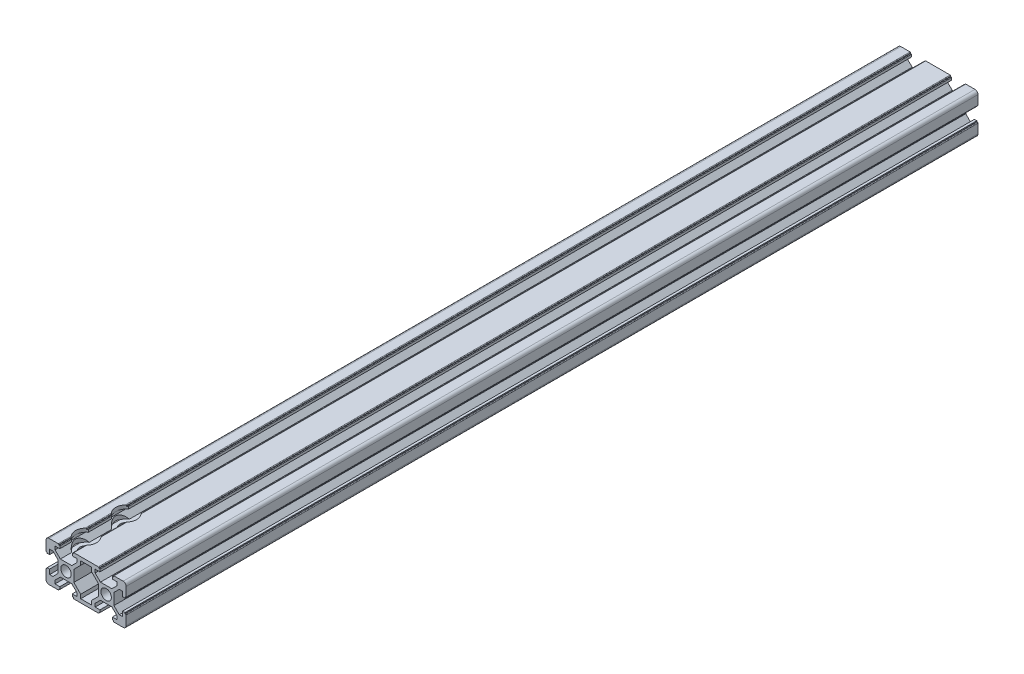
SolidWorks part; units mm, degrees
ref_plane "前视基准面" through (0, 0, 0) normal (0, 0, 1) x (1, 0, 0)
ref_plane "上视基准面" through (0, 0, 0) normal (0, 1, 0) x (1, 0, 0)
ref_plane "右视基准面" through (0, 0, 0) normal (1, 0, 0) x (0, 0, -1)
sketch "草图1" plane through (0, 0, 0) normal (0, 0, 1) x (1, 0, 0)
  line L0 (0, 0) -> (0, -41497.3383) construction
  line L1 (0, 0) -> (41497.3383, 0) construction
  line L2 (-13.9, 0) -> (-13.9, 2.8393)
  line L3 (-13.9, 2.8393) -> (-16.5607, 5.5)
  line L4 (-16.5607, 5.5) -> (-18.2, 5.5)
  line L5 (-18.2, 5.5) -> (-18.2, 3.1)
  line L6 (-18.2, 3.1) -> (-19.4, 3.1)
  line L7 (-19.4, 3.1) -> (-19.4, 3.6)
  line L8 (-19.4, 3.6) -> (-20, 3.6)
  line L9 (-20, 3.6) -> (-20, 10)
  line L10 (-20, 10) -> (-13.6, 10)
  line L11 (-13.6, 10) -> (-13.6, 9.4)
  line L12 (-13.6, 9.4) -> (-13.1, 9.4)
  line L13 (-13.1, 9.4) -> (-13.1, 8.2)
  line L14 (-13.1, 8.2) -> (-15.5, 8.2)
  line L15 (-15.5, 6.5607) -> (-12.8393, 3.9)
  line L16 (-12.8393, 3.9) -> (-7.1607, 3.9)
  line L17 (-4.5, 6.5607) -> (-7.1607, 3.9)
  line L18 (-4.5, 6.5607) -> (-4.5, 8.2)
  line L19 (-4.5, 8.2) -> (-6.9, 8.2)
  line L20 (-6.9, 8.2) -> (-6.9, 9.4)
  line L21 (-6.9, 9.4) -> (-6.4, 9.4)
  line L22 (-6.4, 9.4) -> (-6.4, 10)
  line L23 (-6.4, 10) -> (6.4, 10)
  line L24 (-15.5, 8.2) -> (-15.5, 6.5607)
  line L25 (-10, 0) -> (-20, 10) construction
  line L26 (-6.1, -2.8393) -> (-6.1, 2.8393)
  line L27 (-6.1, 2.8393) -> (-2.7, 6.2393)
  line L28 (-2.7, 6.2393) -> (-2.7, 8.2)
  line L29 (-2.7, 8.2) -> (2.7, 8.2)
  line L30 (-10, 0) -> (0, 10) construction
  line L31 (13.9, 0) -> (13.9, 2.8393)
  line L32 (6.1, -2.8393) -> (6.1, 2.8393)
  line L33 (4.5, 6.5607) -> (7.1607, 3.9)
  line L34 (12.8393, 3.9) -> (7.1607, 3.9)
  line L35 (6.1, 2.8393) -> (2.7, 6.2393)
  line L36 (2.7, 6.2393) -> (2.7, 8.2)
  line L37 (4.5, 6.5607) -> (4.5, 8.2)
  line L38 (6.4, 9.4) -> (6.4, 10)
  line L39 (6.9, 9.4) -> (6.4, 9.4)
  line L40 (6.9, 8.2) -> (6.9, 9.4)
  line L41 (4.5, 8.2) -> (6.9, 8.2)
  line L42 (13.1, 9.4) -> (13.1, 8.2)
  line L43 (13.6, 9.4) -> (13.1, 9.4)
  line L44 (13.6, 10) -> (13.6, 9.4)
  line L45 (20, 10) -> (13.6, 10)
  line L46 (20, 3.6) -> (20, 10)
  line L47 (19.4, 3.6) -> (20, 3.6)
  line L48 (19.4, 3.1) -> (19.4, 3.6)
  line L49 (18.2, 3.1) -> (19.4, 3.1)
  line L50 (18.2, 5.5) -> (18.2, 3.1)
  line L51 (16.5607, 5.5) -> (18.2, 5.5)
  line L52 (13.9, 2.8393) -> (16.5607, 5.5)
  line L53 (15.5, 6.5607) -> (12.8393, 3.9)
  line L54 (15.5, 8.2) -> (15.5, 6.5607)
  line L55 (13.1, 8.2) -> (15.5, 8.2)
  line L56 (15.5, -6.5607) -> (12.8393, -3.9)
  line L57 (13.9, -2.8393) -> (16.5607, -5.5)
  line L58 (16.5607, -5.5) -> (18.2, -5.5)
  line L59 (18.2, -5.5) -> (18.2, -3.1)
  line L60 (18.2, -3.1) -> (19.4, -3.1)
  line L61 (19.4, -3.1) -> (19.4, -3.6)
  line L62 (19.4, -3.6) -> (20, -3.6)
  line L63 (12.8393, -3.9) -> (7.1607, -3.9)
  line L64 (13.9, 0) -> (13.9, -2.8393)
  line L65 (13.1, -8.2) -> (15.5, -8.2)
  line L66 (15.5, -8.2) -> (15.5, -6.5607)
  line L67 (20, -3.6) -> (20, -10)
  line L68 (20, -10) -> (13.6, -10)
  line L69 (13.6, -10) -> (13.6, -9.4)
  line L70 (13.6, -9.4) -> (13.1, -9.4)
  line L71 (13.1, -9.4) -> (13.1, -8.2)
  line L72 (4.5, -8.2) -> (6.9, -8.2)
  line L73 (6.9, -8.2) -> (6.9, -9.4)
  line L74 (6.9, -9.4) -> (6.4, -9.4)
  line L75 (6.4, -9.4) -> (6.4, -10)
  line L76 (4.5, -6.5607) -> (4.5, -8.2)
  line L77 (2.7, -6.2393) -> (2.7, -8.2)
  line L78 (6.1, -2.8393) -> (2.7, -6.2393)
  line L79 (4.5, -6.5607) -> (7.1607, -3.9)
  line L80 (-2.7, -8.2) -> (2.7, -8.2)
  line L81 (-2.7, -6.2393) -> (-2.7, -8.2)
  line L82 (-6.1, -2.8393) -> (-2.7, -6.2393)
  line L83 (-4.5, -6.5607) -> (-7.1607, -3.9)
  line L84 (-4.5, -8.2) -> (-6.9, -8.2)
  line L85 (-4.5, -6.5607) -> (-4.5, -8.2)
  line L86 (-6.4, -10) -> (6.4, -10)
  line L87 (-6.4, -9.4) -> (-6.4, -10)
  line L88 (-6.9, -9.4) -> (-6.4, -9.4)
  line L89 (-6.9, -8.2) -> (-6.9, -9.4)
  line L90 (-13.1, -9.4) -> (-13.1, -8.2)
  line L91 (-13.6, -9.4) -> (-13.1, -9.4)
  line L92 (-13.6, -10) -> (-13.6, -9.4)
  line L93 (-15.5, -8.2) -> (-15.5, -6.5607)
  line L94 (-13.1, -8.2) -> (-15.5, -8.2)
  line L95 (-12.8393, -3.9) -> (-7.1607, -3.9)
  line L96 (-15.5, -6.5607) -> (-12.8393, -3.9)
  line L97 (-13.9, 0) -> (-13.9, -2.8393)
  line L98 (-13.9, -2.8393) -> (-16.5607, -5.5)
  line L99 (-19.4, -3.6) -> (-20, -3.6)
  line L100 (-19.4, -3.1) -> (-19.4, -3.6)
  line L101 (-18.2, -3.1) -> (-19.4, -3.1)
  line L102 (-18.2, -5.5) -> (-18.2, -3.1)
  line L103 (-16.5607, -5.5) -> (-18.2, -5.5)
  line L104 (-20, -3.6) -> (-20, -10)
  line L105 (-20, -10) -> (-13.6, -10)
  circle A0 centre (-10, 0) radius 2.6
  circle A1 centre (10, 0) radius 2.6
  point P50 (0, 8.2)
  point P95 (6.1, 0)
  point P96 (-6.1, 0)
  dimension "D1" = 5.2
  dimension "D2" = 45
  dimension "D3" = 1.5
  dimension "D4" = 20
  dimension "D5" = 40
  dimension "D6" = 0.75
  dimension "D7" = 7.2
  dimension "D8" = 6.2
  dimension "D9" = 6.1
  dimension "D10" = 1.8
  dimension "D11" = 1.2
  dimension "D12" = 12.2
  dimension "D13" = 5.4
  dimension "D14" = 11
  dimension "D15" = 1.5
  dimension "D16" = 0.75
extrude "凸台-拉伸1" add sketch "草图1" along normal mid plane 425
fillet "圆角1" radius 1.5 4 edges at (20, -10, 0) (20, 10, 0) (-20, -10, 0) (-20, 10, 0)
fillet "圆角2" radius 0.3 12 edges at (-6.4, 10, 0) (-13.6, 10, 0) (-20, 3.6, 0) (-20, -3.6, 0) (-13.6, -10, 0) (-6.4, -10, 0) (6.4, -10, 0) (20, -3.6, 0) (20, 3.6, 0) (13.6, -10, 0) (13.6, 10, 0) (6.4, 10, 0)
sketch "草图2" plane through (0, 3.9, 0) normal (0, 1, 0) x (1, 0, 0)
  line L1 (12.8393, -212.5) -> (7.1607, -212.5) construction
  line L2 (-20, -212.5) -> (-20, 212.5) construction
  circle A0 centre (-10, -202.5) radius 3.1
  circle A1 centre (-10, -182.5) radius 3.1
  dimension "D1" = 20
  dimension "D2" = 10
  dimension "D3" = 6.2
  dimension "D4" = 10
extrude "切除-拉伸1" cut sketch "草图2" against normal through all both and the other way through all
sketch "草图3" plane through (0, 3.9, 0) normal (0, 1, 0) x (1, 0, 0)
  circle A0 centre (-10, -182.5) radius 5.25
  circle A1 centre (-10, -202.5) radius 5.25
  dimension "D1" = 10.5
extrude "切除-拉伸2" cut sketch "草图3" along normal through all
equation "\"D6@草图1\"=1/2*\"D3@草图1\""
equation "\"D16@草图1\"=0.5*\"D15@草图1\""
